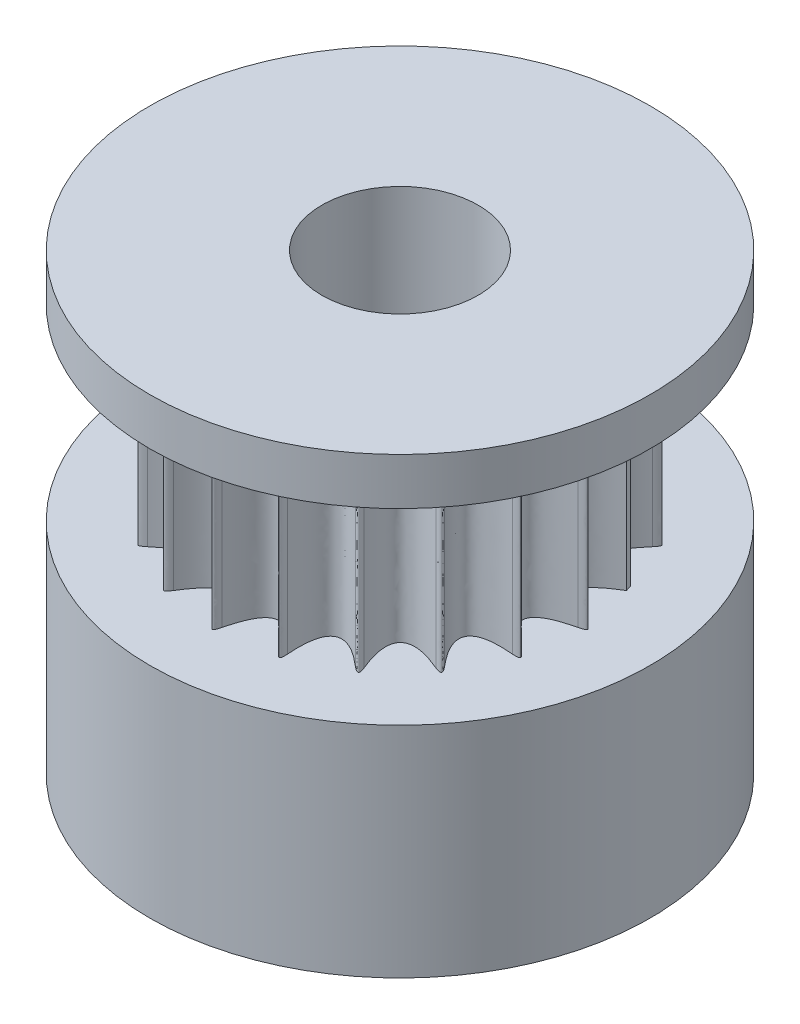
SolidWorks part; units mm, degrees
material "1060 Alloy"
ref_plane "Front Plane" through (0, 0, 0) normal (0, 0, 1) x (1, 0, 0)
ref_plane "Top Plane" through (0, 0, 0) normal (0, 1, 0) x (1, 0, 0)
ref_plane "Right Plane" through (0, 0, 0) normal (1, 0, 0) x (0, 0, -1)
sketch "Sketch1" plane through (0, 0, 0) normal (0, 1, 0) x (1, 0, 0)
  circle A0 centre (0, 0) radius 8
  dimension "D1" = 16
extrude "Boss-Extrude1" add sketch "Sketch1" along normal blind 7
sketch "Sketch2" plane through (0, 7, 0) normal (0, 1, 0) x (1, 0, 0)
  line L0 (0, 8) -> (0, 6) construction
  line L1 (8, 0) -> (6, 0) construction
  line L21 (5.5161, 1.7923) -> (5.7063, 1.8541)
  line L22 (5.7063, 1.8541) -> (5.5161, 1.7923)
  line L23 (5.5161, 1.7923) -> (5.547, 1.6972)
  line L24 (5.5161, 1.7923) -> (5.4852, 1.8874)
  line L25 (-6, 0) -> (-8, 0) construction
  line L31 (0, -6) -> (0, -8) construction
  circle A0 centre (0, 0) radius 8 construction
  circle A1 centre (0, 0) radius 6
  spline S0 degree 2 poles (5.4852, 1.8874) (5.8966, 1.9159) (5.547, 1.6972) knots 0 0 0 1 1 1
  spline S1 degree 2 poles (5.8, 0.1) (6.2, 0) (5.8, -0.1) knots 0 0 0 1 1 1
  spline S2 degree 2 poles (5.547, -1.6972) (5.8966, -1.9159) (5.4852, -1.8874) knots 0 0 0 1 1 1
  spline S3 degree 2 poles (4.7511, -3.3283) (5.0159, -3.6443) (4.6335, -3.4901) knots 0 0 0 1 1 1
  spline S4 degree 2 poles (3.4901, -4.6335) (3.6443, -5.0159) (3.3283, -4.7511) knots 0 0 0 1 1 1
  spline S5 degree 2 poles (1.8874, -5.4852) (1.9159, -5.8966) (1.6972, -5.547) knots 0 0 0 1 1 1
  spline S6 degree 2 poles (0.1, -5.8) (0, -6.2) (-0.1, -5.8) knots 0 0 0 1 1 1
  spline S7 degree 2 poles (-1.6972, -5.547) (-1.9159, -5.8966) (-1.8874, -5.4852) knots 0 0 0 1 1 1
  spline S8 degree 2 poles (-3.3283, -4.7511) (-3.6443, -5.0159) (-3.4901, -4.6335) knots 0 0 0 1 1 1
  spline S9 degree 2 poles (-4.6335, -3.4901) (-5.0159, -3.6443) (-4.7511, -3.3283) knots 0 0 0 1 1 1
  spline S10 degree 2 poles (-5.4852, -1.8874) (-5.8966, -1.9159) (-5.547, -1.6972) knots 0 0 0 1 1 1
  spline S11 degree 2 poles (-5.8, -0.1) (-6.2, 0) (-5.8, 0.1) knots 0 0 0 1 1 1
  spline S12 degree 2 poles (-5.547, 1.6972) (-5.8966, 1.9159) (-5.4852, 1.8874) knots 0 0 0 1 1 1
  spline S13 degree 2 poles (-4.7511, 3.3283) (-5.0159, 3.6443) (-4.6335, 3.4901) knots 0 0 0 1 1 1
  spline S14 degree 2 poles (-3.4901, 4.6335) (-3.6443, 5.0159) (-3.3283, 4.7511) knots 0 0 0 1 1 1
  spline S15 degree 2 poles (-1.8874, 5.4852) (-1.9159, 5.8966) (-1.6972, 5.547) knots 0 0 0 1 1 1
  spline S16 degree 2 poles (-0.1, 5.8) (0, 6.2) (0.1, 5.8) knots 0 0 0 1 1 1
  spline S17 degree 2 poles (1.6972, 5.547) (1.9159, 5.8966) (1.8874, 5.4852) knots 0 0 0 1 1 1
  spline S18 degree 2 poles (3.3283, 4.7511) (3.6443, 5.0159) (3.4901, 4.6335) knots 0 0 0 1 1 1
  spline S19 degree 2 poles (4.6335, 3.4901) (5.0159, 3.6443) (4.7511, 3.3283) knots 0 0 0 1 1 1
  spline S20 degree 2 poles (5.547, 1.6972) (3.7236, 0.6081) (5.8, 0.1) knots 0 0 0 1 1 1
  spline S21 degree 2 poles (5.8, -0.1) (3.7292, -0.5723) (5.547, -1.6972) knots 0 0 0 1 1 1
  spline S22 degree 2 poles (5.4852, -1.8874) (3.3699, -1.6967) (4.7511, -3.3283) knots 0 0 0 1 1 1
  spline S23 degree 2 poles (4.6335, -3.4901) (2.6807, -2.655) (3.4901, -4.6335) knots 0 0 0 1 1 1
  spline S24 degree 2 poles (3.3283, -4.7511) (1.729, -3.3534) (1.8874, -5.4852) knots 0 0 0 1 1 1
  spline S25 degree 2 poles (1.6972, -5.547) (0.6081, -3.7236) (0.1, -5.8) knots 0 0 0 1 1 1
  spline S26 degree 2 poles (-0.1, -5.8) (-0.5723, -3.7292) (-1.6972, -5.547) knots 0 0 0 1 1 1
  spline S27 degree 2 poles (-1.8874, -5.4852) (-1.6967, -3.3699) (-3.3283, -4.7511) knots 0 0 0 1 1 1
  spline S28 degree 2 poles (-3.4901, -4.6335) (-2.655, -2.6807) (-4.6335, -3.4901) knots 0 0 0 1 1 1
  spline S29 degree 2 poles (-4.7511, -3.3283) (-3.3534, -1.729) (-5.4852, -1.8874) knots 0 0 0 1 1 1
  spline S30 degree 2 poles (-5.547, -1.6972) (-3.7236, -0.6081) (-5.8, -0.1) knots 0 0 0 1 1 1
  spline S31 degree 2 poles (-5.8, 0.1) (-3.7292, 0.5723) (-5.547, 1.6972) knots 0 0 0 1 1 1
  spline S32 degree 2 poles (-5.4852, 1.8874) (-3.3699, 1.6967) (-4.7511, 3.3283) knots 0 0 0 1 1 1
  spline S33 degree 2 poles (-4.6335, 3.4901) (-2.6807, 2.655) (-3.4901, 4.6335) knots 0 0 0 1 1 1
  spline S34 degree 2 poles (-3.3283, 4.7511) (-1.729, 3.3534) (-1.8874, 5.4852) knots 0 0 0 1 1 1
  spline S35 degree 2 poles (-1.6972, 5.547) (-0.6081, 3.7236) (-0.1, 5.8) knots 0 0 0 1 1 1
  spline S36 degree 2 poles (0.1, 5.8) (0.5723, 3.7292) (1.6972, 5.547) knots 0 0 0 1 1 1
  spline S37 degree 2 poles (1.8874, 5.4852) (1.6967, 3.3699) (3.3283, 4.7511) knots 0 0 0 1 1 1
  spline S38 degree 2 poles (3.4901, 4.6335) (2.655, 2.6807) (4.6335, 3.4901) knots 0 0 0 1 1 1
  spline S39 degree 2 poles (4.7511, 3.3283) (3.3534, 1.729) (5.4852, 1.8874) knots 0 0 0 1 1 1
  point P32 (0, 0)
  point P94 (0, 0)
  point P153 (0, 0)
  dimension "D1" = 12
  dimension "D3" = 0.1
  dimension "D4" = 0.1
  dimension "D5" = 0.2
extrude "Boss-Extrude2" add sketch "Sketch2" along normal blind 6 contours S39 S19 S38 S18 S37 S17 S36 S16 S35 S15 S34 S14 S33 S13 S32 S12 S31 S11 S30 S10 S29 S9 S28 S8 S27 S7 S26 S6 S25 S5 S24 S4 S23 S3
sketch "Sketch3" plane through (0, 13, 0) normal (0, 1, 0) x (1, 0, 0)
  circle A0 centre (0, 0) radius 8 construction
  circle A1 centre (0, 0) radius 8
extrude "Boss-Extrude3" add sketch "Sketch3" along normal blind 1.5
sketch "Sketch4" plane through (0, 14.5, 0) normal (0, 1, 0) x (1, 0, 0)
  circle A0 centre (0, 0) radius 2.5
  dimension "D1" = 5
extrude "Cut-Extrude1" cut sketch "Sketch4" against normal through all
